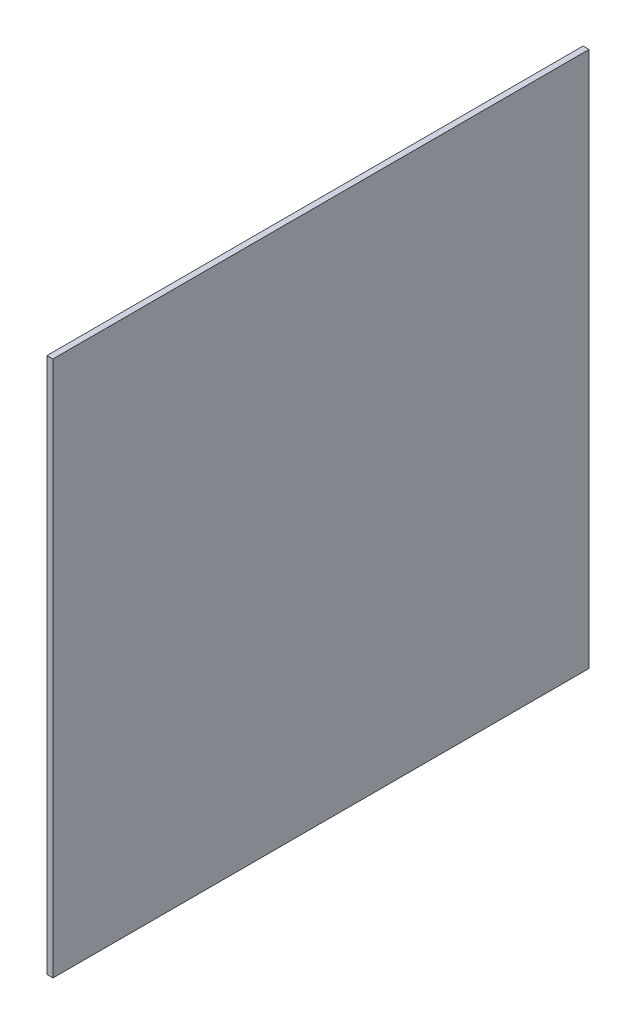
SolidWorks part; units mm, degrees
material "Acrylic (Medium-high impact)"
ref_plane "Front Plane" through (0, 0, 0) normal (0, 0, 1) x (1, 0, 0)
ref_plane "Top Plane" through (0, 0, 0) normal (0, 1, 0) x (1, 0, 0)
ref_plane "Right Plane" through (0, 0, 0) normal (1, 0, 0) x (0, 0, -1)
sketch "Sketch1" plane through (0, 0, 0) normal (1, 0, 0) x (0, 0, -1)
  line L0 (-285.75, 0) -> (285.75, 0) construction
  line L5 (0, -285.75) -> (0, 285.75) construction
  point P0 (0, 0)
  point P3 (0, 0)
  point P8 (0, 0)
  dimension "Width" = 571.5
  dimension "Length" = 571.5
sketch "Sketch2" plane through (0, 0, 0) normal (0, 0, 1) x (1, 0, 0)
  line L0 (3.175, 0) -> (-3.175, 0) construction
  point P4 (0, 0)
  dimension "Thickness" = 6.35
sketch "Sketch3" plane through (0, 0, 0) normal (1, 0, 0) x (0, 0, -1)
  line L1 (-285.75, -285.75) -> (285.75, -285.75)
  line L2 (-285.75, -285.75) -> (-285.75, 285.75)
  line L3 (-285.75, 285.75) -> (285.75, 285.75)
  line L4 (285.75, -285.75) -> (285.75, 285.75)
  line L5 (-285.75, -285.75) -> (285.75, 285.75) construction
  line L6 (-285.75, 285.75) -> (285.75, -285.75) construction
  point P0 (0, 0)
extrude "Boss-Extrude1" add sketch "Sketch3" along normal up to vertex (3.175 mm away) and the other way up to vertex (3.175 mm away) up to point (3.175, 0, 0) other way up to point (-3.175, 0, 0)
ref_plane "Contact Plane 1" through (-3.175, 0, 0) normal (-1, 0, 0) x (0, 0, 1)
ref_plane "Contact Plane 2" through (0, -285.75, 0) normal (0, -1, 0) x (-1, 0, 0)
sketch "Sketch4" plane through (-3.175, 0, 0) normal (-1, 0, 0) x (0, 0, 1)
  line L0 (-285.75, 285.75) -> (285.75, 285.75) construction
  line L1 (285.75, -285.75) -> (-285.75, -285.75) construction
  circle A0 centre (0, -184.15) radius 25.4
  point P4 (0, 285.75)
  dimension "D1" = 50.8
  dimension "D2" = 101.6
extrude "Cut-Extrude1" [suppressed] cut sketch "Sketch4" against normal through all
